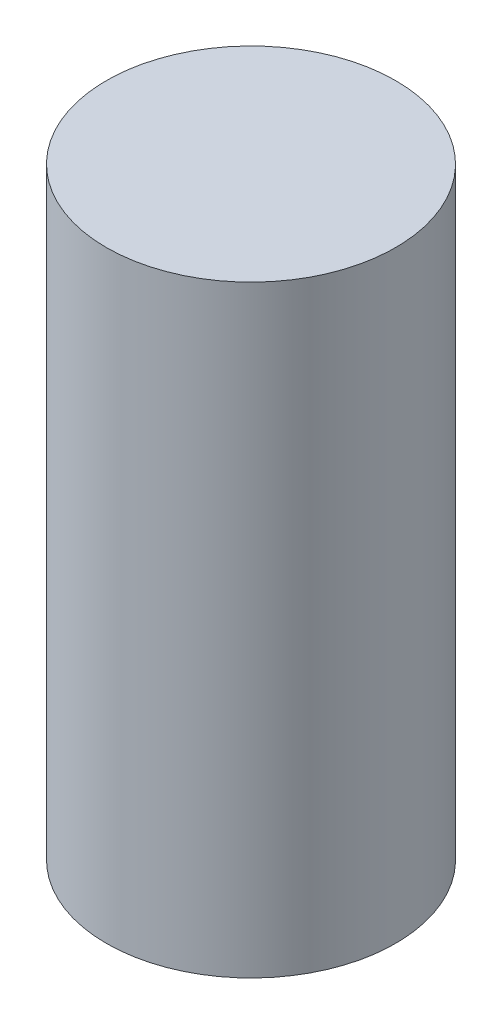
SolidWorks part; units mm, degrees
ref_plane "Front Plane" through (0, 0, 0) normal (0, 0, 1) x (1, 0, 0)
ref_plane "Top Plane" through (0, 0, 0) normal (0, 1, 0) x (1, 0, 0)
ref_plane "Right Plane" through (0, 0, 0) normal (1, 0, 0) x (0, 0, -1)
sketch "Sketch1" plane through (0, 0, 0) normal (0, 1, 0) x (1, 0, 0)
  circle A0 centre (0, 0) radius 0.48
extrude "Boss-Extrude1" add sketch "Sketch1" along normal blind 2
